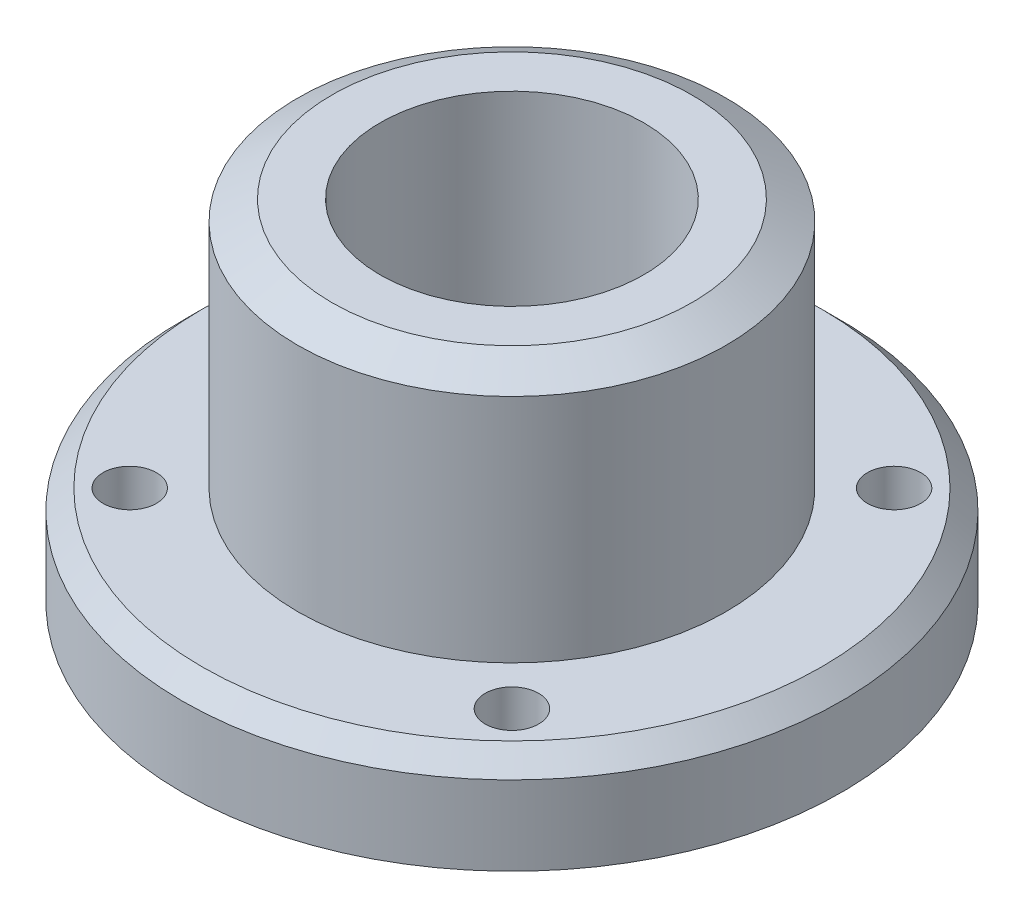
SolidWorks part; units mm, degrees
ref_plane "Front Plane" through (0, 0, 0) normal (0, 0, 1) x (1, 0, 0)
ref_plane "Top Plane" through (0, 0, 0) normal (0, 1, 0) x (1, 0, 0)
ref_plane "Right Plane" through (0, 0, 0) normal (1, 0, 0) x (0, 0, -1)
ref_plane "Plane1" through (0, 11.5, 0) normal (0, -1, 0) x (1, 0, 0)
sketch "Sketch1" plane through (0, 11.5, 0) normal (0, -1, 0) x (1, 0, 0)
  circle A0 centre (0, 0) radius 50
  dimension "D1" = 100
extrude "Boss-Extrude1" add sketch "Sketch1" against normal blind 15
sketch "Sketch3" plane through (0, 11.5, 0) normal (0, -1, 0) x (1, 0, 0)
  circle A0 centre (0, 0) radius 3
  point P3 (0, 0)
extrude "Cut-Extrude2" [suppressed] cut sketch "Sketch3" against normal through all
sketch "Sketch4" plane through (0, 11.5, 0) normal (0, -1, 0) x (1, 0, 0)
  circle A0 centre (-150.0571, 33.5) radius 3
extrude "Cut-Extrude3" [suppressed] cut sketch "Sketch4" against normal through all
sketch "Sketch5" plane through (0, 26.5, 0) normal (0, 1, 0) x (-1, 0, 0)
  line L0 (29.15, 0) -> (-29.15, 0) construction
  line L1 (0, 29.15) -> (0, -29.15) construction
  circle A0 centre (40, 0) radius 3
  dimension "D1" = 6
  dimension "D2" = 40
extrude "Cut-Extrude4" [suppressed] cut sketch "Sketch5" against normal through all
sketch "Sketch6" plane through (0, 26.5, 0) normal (0, 1, 0) x (-1, 0, 0)
  circle A0 centre (0, 0) radius 32.5
  point P3 (187.5713, 0)
  dimension "D1" = 65
extrude "Boss-Extrude2" add sketch "Sketch6" along normal blind 35
sketch "Sketch7" plane through (0, 61.5, 0) normal (0, 1, 0) x (-1, 0, 0)
  circle A0 centre (0, 0) radius 32.5
  point P3 (0, 0)
  dimension "D1" = 65
extrude "Boss-Extrude3" add sketch "Sketch7" along normal blind 3 draft 60
sketch "Sketch9" plane through (0, 11.5, 0) normal (0, -1, 0) x (1, 0, 0)
  circle A0 centre (0, 0) radius 25.75
  point P2 (0, 0)
extrude "Cut-Extrude5" cut sketch "Sketch9" against normal blind 10.2
sketch "Sketch10" plane through (0, 21.7, 0) normal (0, -1, 0) x (1, 0, 0)
  circle A0 centre (0, 0) radius 20
  point P2 (0, 0)
  dimension "D1" = 40
extrude "Cut-Extrude6" cut sketch "Sketch10" against normal through all
extrude "Cut-Extrude7" cut sketch "Sketch11" along normal blind 40
sketch "Sketch11" plane through (389.1601, 11.5, 0) normal (0, 1, 0) x (1, 0, 0)
  line L0 (-389.1601, 0) -> (-360.1687, 28.9914) construction
  line L1 (-389.1601, -29.15) -> (-389.1601, 29.15) construction
  circle A4 centre (-389.1601, 0) radius 41 construction
  circle A5 centre (-360.1687, 28.9914) radius 4.05
  point P2 (-576.7314, 0)
  point P12 (-576.7314, 0)
  dimension "D1" = 8.1
  dimension "D2" = 82
  dimension "D3" = 45
pattern_circular "CirPattern1" count 4 over 360 about axis through (0, 0, 0) along (0, 1, 0) of "Cut-Extrude7"
chamfer "Chamfer1" distance 3 angle 45 1 edges at (0, 26.5, 50)
